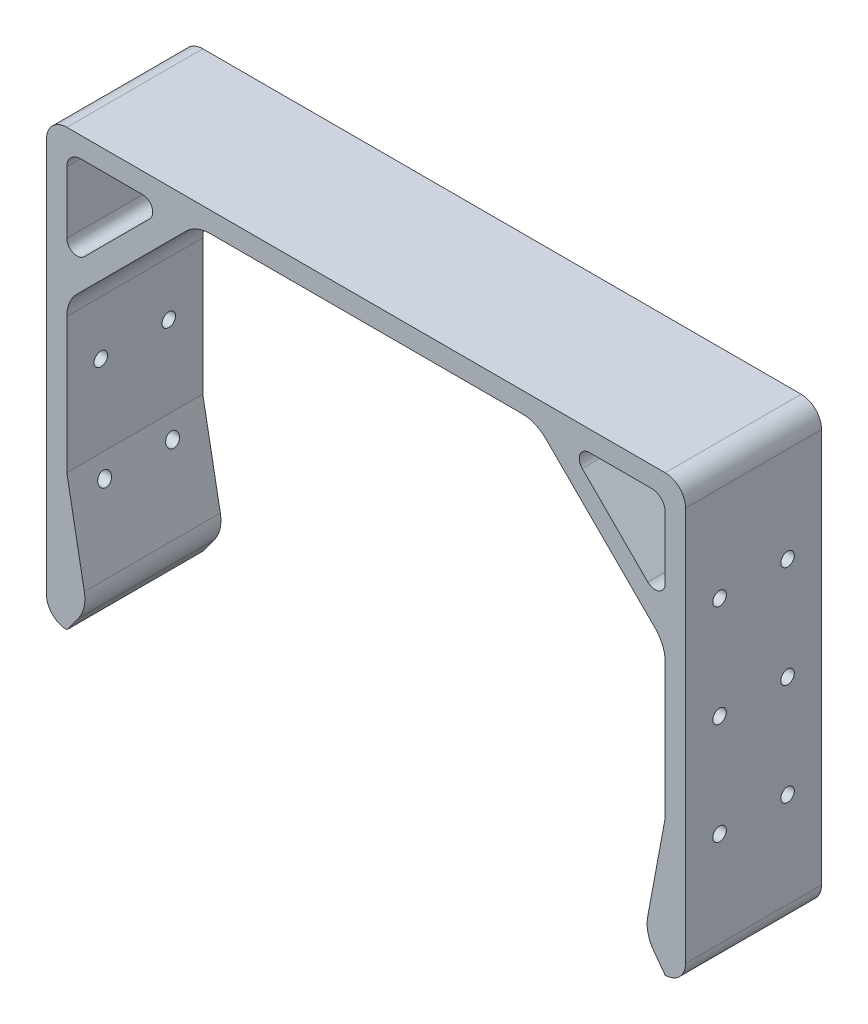
SolidWorks part; units mm, degrees
ref_plane "Front Plane" through (0, 0, 0) normal (0, 0, 1) x (1, 0, 0)
ref_plane "Top Plane" through (0, 0, 0) normal (0, 1, 0) x (1, 0, 0)
ref_plane "Right Plane" through (0, 0, 0) normal (1, 0, 0) x (0, 0, -1)
sketch "Sketch1" plane through (0, 0, 0) normal (0, 0, 1) x (1, 0, 0)
  line L0 (-44, -32) -> (-44, 7.9289)
  line L1 (-44, -32) -> (44, -32) construction
  line L2 (-47, -29) -> (-47, 29)
  line L3 (-44, 32) -> (44, 32)
  line L4 (47, -29) -> (47, 29)
  line L5 (0, 32) -> (0, -32) construction
  line L6 (-47, 0) -> (47, 0) construction
  line L7 (-42, 29) -> (-32.864, 29)
  line L8 (44, 27) -> (44, 17.864)
  line L9 (-44, -32) -> (-42.3204, -29.7285)
  line L10 (-41.4251, -25.8414) -> (-44, -12)
  line L11 (41.4251, -25.8414) -> (44, -12)
  line L12 (44, -32) -> (42.3204, -29.7285)
  line L13 (-31.8033, 26.4393) -> (-41.4393, 16.8033)
  line L14 (-26.4645, 27.5355) -> (-42.5355, 11.4645)
  line L15 (-22.9289, 29) -> (22.9289, 29)
  line L16 (-44, 17.864) -> (-44, 27)
  line L17 (26.4645, 27.5355) -> (42.5355, 11.4645)
  line L18 (31.8033, 26.4393) -> (41.4393, 16.8033)
  line L19 (32.864, 29) -> (42, 29)
  line L20 (44, 7.9289) -> (44, -32)
  arc A0 (-44, -32) -> (-47, -29) centre (-44, -29) cw
  arc A1 (44, -32) -> (47, -29) centre (44, -29) ccw
  arc A2 (44, 32) -> (47, 29) centre (44, 29) cw
  arc A3 (-47, 29) -> (-44, 32) centre (-44, 29) cw
  arc A4 (42, 29) -> (44, 27) centre (42, 27) cw
  arc A5 (-44, 27) -> (-42, 29) centre (-42, 27) cw
  arc A6 (-42.3204, -29.7285) -> (-41.4251, -25.8414) centre (-46.3407, -26.7558) ccw
  arc A7 (42.3204, -29.7285) -> (41.4251, -25.8414) centre (46.3407, -26.7558) cw
  arc A8 (-41.4393, 16.8033) -> (-44, 17.864) centre (-42.5, 17.864) cw
  arc A9 (-31.8033, 26.4393) -> (-32.864, 29) centre (-32.864, 27.5) ccw
  arc A10 (-26.4645, 27.5355) -> (-22.9289, 29) centre (-22.9289, 24) cw
  arc A11 (-42.5355, 11.4645) -> (-44, 7.9289) centre (-39, 7.9289) ccw
  arc A12 (42.5355, 11.4645) -> (44, 7.9289) centre (39, 7.9289) cw
  arc A13 (26.4645, 27.5355) -> (22.9289, 29) centre (22.9289, 24) ccw
  arc A14 (41.4393, 16.8033) -> (44, 17.864) centre (42.5, 17.864) ccw
  arc A15 (31.8033, 26.4393) -> (32.864, 29) centre (32.864, 27.5) cw
  point P0 (0, 0)
  point P6 (-47, -32)
  point P12 (47, 32)
  point P15 (-47, 32)
  point P26 (-41.0273, -27.9797)
  point P31 (41.0273, -27.9797)
  point P32 (47, -32)
  point P39 (-44, 14.2426)
  point P44 (-25, 29)
  dimension "D3" = 3
  dimension "D4" = 2
  dimension "D8" = 5
  dimension "D13" = 1.5
  dimension "D14" = 5
  dimension "D1" = 94
  dimension "D2" = 64
  dimension "D5" = 53.52
  dimension "D6" = 20
  dimension "D7" = 5
  dimension "D9" = 3
  dimension "D10" = 3
  dimension "D11" = 25
  dimension "D12" = 45
extrude "Boss-Extrude2" add sketch "Sketch1" along normal blind 20 contours L9 A6 L10 L0 | L0 A5 L7 A4 L8 A1 L4 A2 L3 A3 L2 A0 | A7 L12 L8 L11
sketch "Sketch2" plane through (-47, 0, 0) normal (-1, 0, 0) x (0, 0, 1)
  line L0 (0, 0) -> (20, 0) construction
  line L1 (5, 0) -> (5, 15) construction
  line L4 (0, 29) -> (0, -29)
  line L5 (0, -29) -> (20, -29)
  line L6 (20, -29) -> (20, 29)
  line L7 (20, 29) -> (0, 29)
  line L8 (0, 29) -> (0, -29) construction
  line L9 (0, -29) -> (20, -29) construction
  line L10 (20, -29) -> (20, 29) construction
  line L11 (20, 29) -> (0, 29) construction
  circle A0 centre (5, 15) radius 1
  circle A1 centre (15, 15) radius 1
  circle A2 centre (15, 0) radius 1
  circle A3 centre (15, -15) radius 1
  circle A4 centre (5, 0) radius 1
  circle A5 centre (5, -15) radius 1
  dimension "D3" = 2
  dimension "D2" = 5
  dimension "D4" = 15
  dimension "D1" = 0
  dimension "D5" = 2
  dimension "D6" = 3
extrude "Cut-Extrude1" cut sketch "Sketch2" against normal blind 5
mirror "Mirror1" about plane through (0, 0, 0) normal (1, 0, 0) of "Cut-Extrude1"
